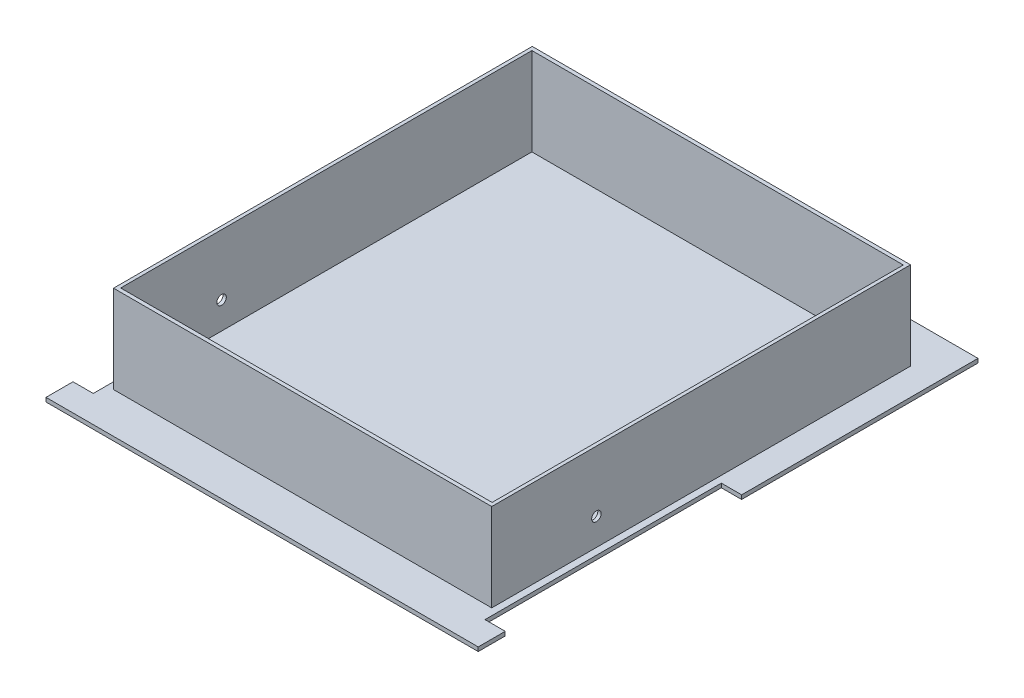
SolidWorks part; units mm, degrees
material "7050-T7651"
ref_plane "Front Plane" through (0, 0, 0) normal (0, 0, 1) x (1, 0, 0)
ref_plane "Top Plane" through (0, 0, 0) normal (0, 1, 0) x (1, 0, 0)
ref_plane "Right Plane" through (0, 0, 0) normal (1, 0, 0) x (0, 0, -1)
sketch "Sketch1" plane through (0, 0, 0) normal (0, 1, 0) x (1, 0, 0)
  line L1 (-160, 185) -> (160, 185)
  line L2 (-160, 185) -> (-160, -185)
  line L3 (-160, -185) -> (160, -185)
  line L4 (160, 185) -> (160, -185)
  line L5 (-160, 185) -> (160, -185) construction
  line L6 (-160, -185) -> (160, 185) construction
  point P0 (0, 0)
  dimension "D1" = 370
  dimension "D2" = 320
extrude "Boss-Extrude1" add sketch "Sketch1" along normal blind 3
sketch "Sketch2" plane through (0, 3, 0) normal (0, 1, 0) x (1, 0, 0)
  line L1 (-140, 155) -> (140, 155)
  line L2 (-140, 155) -> (-140, -155)
  line L3 (-140, -155) -> (140, -155)
  line L4 (140, 155) -> (140, -155)
  line L5 (-140, 155) -> (140, -155) construction
  line L6 (-140, -155) -> (140, 155) construction
  line L7 (-137.5, 152.2321) -> (137.5, 152.2321)
  line L8 (-137.5, 152.2321) -> (-137.5, -152.2321)
  line L9 (-137.5, -152.2321) -> (137.5, -152.2321)
  line L10 (137.5, 152.2321) -> (137.5, -152.2321)
  line L11 (-137.5, 152.2321) -> (137.5, -152.2321) construction
  line L12 (-137.5, -152.2321) -> (137.5, 152.2321) construction
  point P0 (0, 0)
  point P6 (0, 0)
  dimension "D1" = 310
  dimension "D2" = 2.5
  dimension "D3" = 280
extrude "Boss-Extrude2" add sketch "Sketch2" along normal blind 65
sketch "Sketch4" plane through (0, 3, 0) normal (0, 1, 0) x (1, 0, 0)
  line L0 (-160, 185) -> (-160, -185) construction
  line L1 (-160, -165) -> (-160, 10)
  line L2 (-160, 10) -> (-145, 10)
  line L8 (-145, 10) -> (-145, -165)
  line L9 (-145, -165) -> (-160, -165)
  line L10 (-160, -185) -> (160, -185) construction
  dimension "D1" = 175
  dimension "D2" = 15
  dimension "D4" = 20
extrude "Cut-Extrude2" cut sketch "Sketch4" against normal blind 40
mirror "Mirror3" about plane through (0, 0, 0) normal (1, 0, 0) of "Cut-Extrude2"
sketch "Sketch5" plane through (140, 0, 0) normal (1, 0, 0) x (0, 0, -1)
  line L0 (-155, 3) -> (155, 3) construction
  circle A0 centre (-77.5, 23) radius 3.5
  dimension "D1" = 7
  dimension "D2" = 20
extrude "Cut-Extrude3" cut sketch "Sketch5" against normal through all
sketch "Sketch6" plane through (0, 0, 0) normal (0, -1, 0) x (1, 0, 0)
  line L0 (160, -185) -> (-160, -185) construction
  line L1 (-100, -97) -> (-62, -97)
  line L2 (-100, -97) -> (-100, -135)
  line L3 (-100, -135) -> (-62, -135)
  line L4 (-62, -97) -> (-62, -135)
  line L5 (62, -97) -> (100, -97)
  line L6 (62, -97) -> (62, -135)
  line L7 (62, -135) -> (100, -135)
  line L8 (100, -97) -> (100, -135)
  line L9 (160, -10) -> (160, -185) construction
  line L10 (-160, -185) -> (-160, -10) construction
  dimension "D1" = 38
  dimension "D2" = 38
  dimension "D3" = 50
  dimension "D4" = 50
  dimension "D5" = 60
  dimension "D6" = 60
extrude "Cut-Extrude5" cut sketch "Sketch6" against normal blind 2
